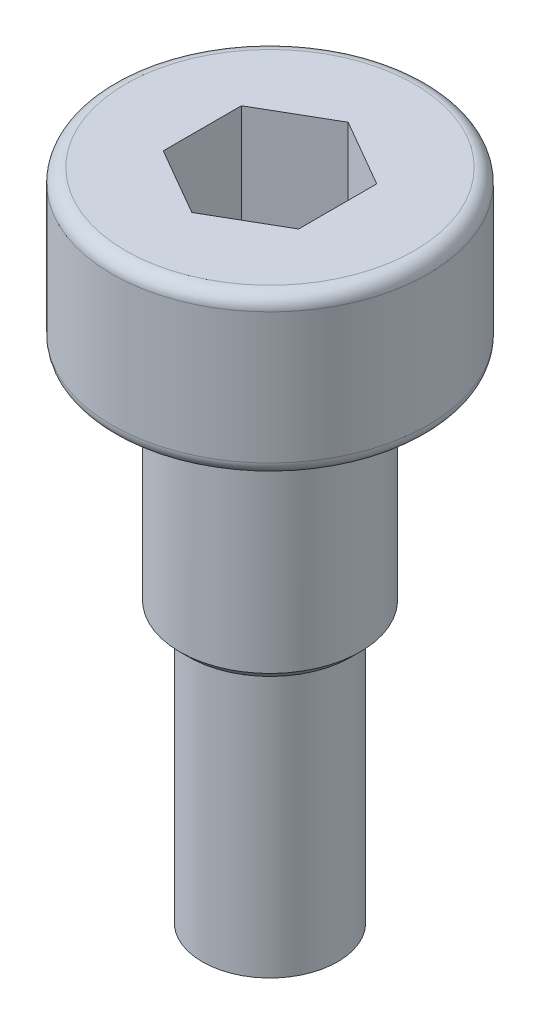
SolidWorks part; units mm, degrees
ref_plane "前视基准面" through (0, 0, 0) normal (0, 0, 1) x (1, 0, 0)
ref_plane "上视基准面" through (0, 0, 0) normal (0, 1, 0) x (1, 0, 0)
ref_plane "右视基准面" through (0, 0, 0) normal (1, 0, 0) x (0, 0, -1)
sketch "草图1" plane through (0, 0, 0) normal (0, 0, 1) x (1, 0, 0)
  line L0 (0, 13.2929) -> (0, -24.3848) construction
  line L1 (0, 9.6164) -> (-3.5, 9.6164)
  line L2 (-3.5, 9.6164) -> (-3.5, 6.1164)
  line L3 (-3.5, 6.1164) -> (-2, 6.1164)
  line L4 (-2, 6.1164) -> (-2, 1.1164)
  line L5 (-2, 1.1164) -> (-1.5, 1.1164)
  line L6 (-1.5, 1.1164) -> (-1.5, -4.8836)
  line L7 (-1.5, -4.8836) -> (0, -4.8836)
  line L8 (0, 9.6164) -> (0, -4.8836)
  dimension "D1" = 3
  dimension "D2" = 6
  dimension "D3" = 4
  dimension "D4" = 7
  dimension "D5" = 3.5
  dimension "D6" = 5
revolve "旋转1" add sketch "草图1" angle 360 about L0
cosmetic thread "装饰螺纹线1" parameters "D2"=2.459
fillet "圆角1" radius 0.3 2 edges at (0, 6.1164, 3.5) (0, 9.6164, 3.5)
sketch "草图2" plane through (0, 9.6164, 0) normal (0, 1, 0) x (1, 0, 0)
  line L1 (1.5, 0.866) -> (0, 1.7321)
  line L2 (0, 1.7321) -> (-1.5, 0.866)
  line L3 (-1.5, 0.866) -> (-1.5, -0.866)
  line L4 (-1.5, -0.866) -> (0, -1.7321)
  line L5 (0, -1.7321) -> (1.5, -0.866)
  line L6 (1.5, -0.866) -> (1.5, 0.866)
  circle A0 centre (0, 0) radius 1.5 construction
  dimension "D1" = 3
extrude "切除-拉伸1" cut sketch "草图2" against normal blind 2.4
chamfer "倒角1" distance 0.2 angle 45 1 edges at (0, 1.1164, 2)
